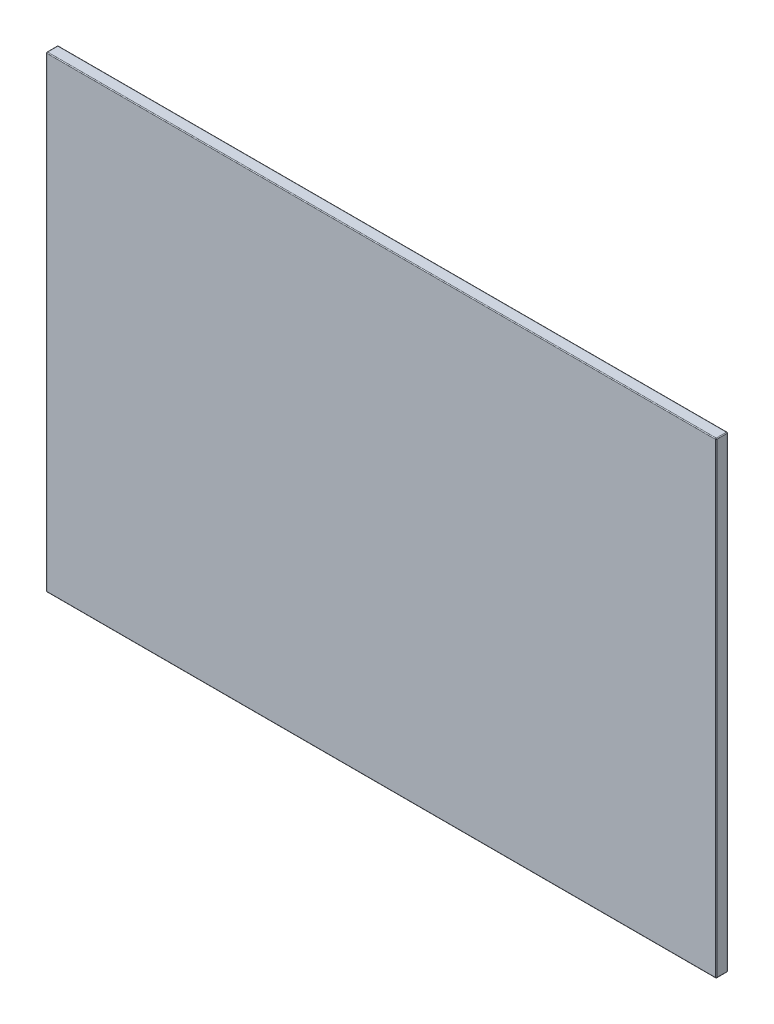
SolidWorks part; units mm, degrees
material "Oak"
ref_plane "Ön Düzlem" through (0, 0, 0) normal (0, 0, 1) x (1, 0, 0)
ref_plane "Üst Düzlem" through (0, 0, 0) normal (0, 1, 0) x (1, 0, 0)
ref_plane "Sağ Düzlem" through (0, 0, 0) normal (1, 0, 0) x (0, 0, -1)
sketch "Sketch1" plane through (0, 0, 0) normal (0, 0, 1) x (1, 0, 0)
  line L1 (-430, 300) -> (430, 300)
  line L2 (-430, 300) -> (-430, -300)
  line L3 (-430, -300) -> (430, -300)
  line L4 (430, 300) -> (430, -300)
  point P4 (0, 300)
  point P6 (-430, 0)
  dimension "D1" = 860
  dimension "D2" = 600
extrude "Boss-Extrude1" add sketch "Sketch1" along normal blind 15
fillet "Fillet1" radius 1 11 edges at (0, 300, 15) (430, 0, 15) (0, -300, 15) (-430, 0, 15) (-430, 300, 7.5) (-430, 0, 0) (430, -300, 7.5) (0, -300, 0) (430, 0, 0) (0, 300, 0) (430, 300, 7.5)
